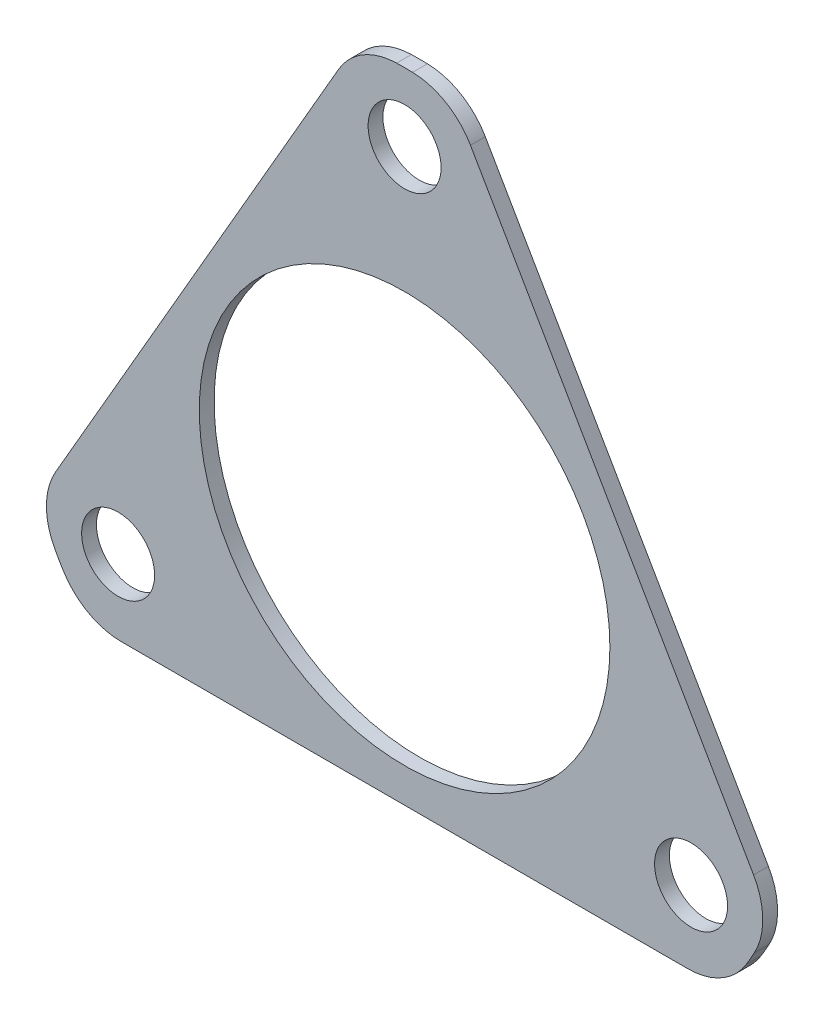
SolidWorks part; units mm, degrees
ref_plane "Спереди" through (0, 0, 0) normal (0, 0, 1) x (1, 0, 0)
ref_plane "Сверху" through (0, 0, 0) normal (0, 1, 0) x (1, 0, 0)
ref_plane "Справа" through (0, 0, 0) normal (1, 0, 0) x (0, 0, -1)
sketch "Sketch1" plane through (0, 0, 0) normal (0, 0, 1) x (1, 0, 0)
  line L0 (3.9, 6.755) -> (7.8, 0) construction
  line L2 (5.85, 10.1325) -> (11.7, 0) construction
  line L4 (7.8, 13.51) -> (15.6, 0) construction
  circle A61 centre (0, 0) radius 20
  circle A131 centre (0, 0) radius 1.25
  circle A484 centre (3.9, 0) radius 1.25
  circle A485 centre (7.8, 0) radius 1.25
  circle A486 centre (11.7, 0) radius 1.25
  circle A487 centre (15.6, 0) radius 1.25
  circle A488 centre (1.95, -3.3775) radius 1.25
  circle A489 centre (3.9, -6.755) radius 1.25
  circle A490 centre (5.85, -10.1325) radius 1.25
  circle A491 centre (7.8, -13.51) radius 1.25
  circle A492 centre (-1.95, -3.3775) radius 1.25
  circle A493 centre (-3.9, -6.755) radius 1.25
  circle A494 centre (-5.85, -10.1325) radius 1.25
  circle A495 centre (-7.8, -13.51) radius 1.25
  circle A496 centre (-3.9, 0) radius 1.25
  circle A497 centre (-7.8, 0) radius 1.25
  circle A498 centre (-11.7, 0) radius 1.25
  circle A499 centre (-15.6, 0) radius 1.25
  circle A500 centre (-1.95, 3.3775) radius 1.25
  circle A501 centre (-3.9, 6.755) radius 1.25
  circle A502 centre (-5.85, 10.1325) radius 1.25
  circle A503 centre (-7.8, 13.51) radius 1.25
  circle A504 centre (1.95, 3.3775) radius 1.25
  circle A505 centre (3.9, 6.755) radius 1.25
  circle A506 centre (5.85, 10.1325) radius 1.25
  circle A507 centre (7.8, 13.51) radius 1.25
  circle A508 centre (5.85, 3.3775) radius 1.25
  circle A509 centre (7.8, 6.755) radius 1.25
  circle A510 centre (9.75, 3.3775) radius 1.25
  circle A511 centre (11.7, 6.755) radius 1.25
  circle A512 centre (9.7491, 10.1341) radius 1.25
  circle A513 centre (13.6509, 3.3759) radius 1.25
  circle A514 centre (5.85, -3.3791) radius 1.25
  circle A515 centre (9.75, -3.3791) radius 1.25
  circle A516 centre (7.8, -6.7566) radius 1.25
  circle A517 centre (11.7, -6.7566) radius 1.25
  circle A518 centre (9.7491, -10.1356) radius 1.25
  circle A519 centre (13.6509, -3.3775) radius 1.25
  circle A520 centre (-0.0013, -6.7573) radius 1.25
  circle A521 centre (1.9487, -10.1348) radius 1.25
  circle A522 centre (-1.9513, -10.1348) radius 1.25
  circle A523 centre (-0.0013, -13.5123) radius 1.25
  circle A524 centre (-3.9032, -13.5123) radius 1.25
  circle A525 centre (3.9005, -13.5123) radius 1.25
  circle A526 centre (-5.8527, -3.3791) radius 1.25
  circle A527 centre (-7.8027, -6.7566) radius 1.25
  circle A528 centre (-9.7527, -3.3791) radius 1.25
  circle A529 centre (-11.7027, -6.7566) radius 1.25
  circle A530 centre (-13.6536, -3.3775) radius 1.25
  circle A531 centre (-9.7518, -10.1356) radius 1.25
  circle A532 centre (-5.8527, 3.3775) radius 1.25
  circle A533 centre (-9.7527, 3.3775) radius 1.25
  circle A534 centre (-7.8027, 6.755) radius 1.25
  circle A535 centre (-11.7027, 6.755) radius 1.25
  circle A536 centre (-9.7518, 10.1341) radius 1.25
  circle A537 centre (-13.6536, 3.3759) radius 1.25
  circle A538 centre (-0.0014, 6.7558) radius 1.25
  circle A539 centre (-1.9514, 10.1333) radius 1.25
  circle A540 centre (1.9486, 10.1333) radius 1.25
  circle A541 centre (-0.0014, 13.5108) radius 1.25
  circle A542 centre (3.9005, 13.5108) radius 1.25
  circle A543 centre (-3.9032, 13.5108) radius 1.25
  circle A544 centre (13.65, -1.1258) radius 2.2517 construction
  circle A545 centre (11.7009, -4.5044) radius 2.2522 construction
  circle A546 centre (9.75, -7.8834) radius 2.2522 construction
  circle A547 centre (7.7987, -11.2591) radius 2.2509 construction
  circle A548 centre (13.65, -1.1258) radius 0.65
  circle A549 centre (11.7009, -4.5044) radius 0.65
  circle A550 centre (9.75, -7.8834) radius 0.65
  circle A551 centre (7.7987, -11.2591) radius 0.65
  circle A552 centre (9.75, -1.1258) radius 0.65
  circle A553 centre (7.8009, -4.5044) radius 0.65
  circle A554 centre (5.85, -7.8834) radius 0.65
  circle A555 centre (3.8987, -11.2591) radius 0.65
  circle A556 centre (5.85, -1.1258) radius 0.65
  circle A557 centre (3.9009, -4.5044) radius 0.65
  circle A558 centre (1.95, -7.8834) radius 0.65
  circle A559 centre (-0.0013, -11.2591) radius 0.65
  circle A560 centre (1.95, -1.1258) radius 0.65
  circle A561 centre (0.0009, -4.5044) radius 0.65
  circle A562 centre (-1.95, -7.8834) radius 0.65
  circle A563 centre (-3.9013, -11.2591) radius 0.65
  circle A564 centre (-1.95, -1.1258) radius 0.65
  circle A565 centre (-3.8991, -4.5044) radius 0.65
  circle A566 centre (-5.85, -7.8834) radius 0.65
  circle A567 centre (-7.8013, -11.2591) radius 0.65
  circle A568 centre (-5.85, -1.1258) radius 0.65
  circle A569 centre (-7.7991, -4.5044) radius 0.65
  circle A570 centre (-9.75, -7.8834) radius 0.65
  circle A572 centre (-9.75, -1.1258) radius 0.65
  circle A573 centre (-11.6991, -4.5044) radius 0.65
  circle A576 centre (-13.65, -1.1258) radius 0.65
  circle A587 centre (0, 2.2517) radius 2.2517 construction
  circle A588 centre (0, 2.2517) radius 0.65
  circle A589 centre (3.9, 2.2517) radius 0.65
  circle A590 centre (7.8, 2.2517) radius 0.65
  circle A591 centre (11.7, 2.2517) radius 0.65
  circle A592 centre (15.6, 2.2517) radius 0.65
  circle A593 centre (1.9491, 5.6297) radius 2.2522 construction
  circle A594 centre (1.9491, 5.6297) radius 0.65
  circle A595 centre (5.8491, 5.6297) radius 0.65
  circle A596 centre (9.7491, 5.6297) radius 0.65
  circle A597 centre (13.6491, 5.6297) radius 0.65
  circle A598 centre (3.8991, 9.0072) radius 2.2522 construction
  circle A599 centre (3.8991, 9.0072) radius 0.65
  circle A600 centre (7.7991, 9.0072) radius 0.65
  circle A601 centre (11.6991, 9.0072) radius 0.65
  circle A602 centre (5.85, 12.3842) radius 2.2517 construction
  circle A603 centre (5.85, 12.3842) radius 0.65
  circle A604 centre (9.75, 12.3842) radius 0.65
  circle A605 centre (5.85, -14.6358) radius 0.65
  circle A606 centre (1.9509, -14.6353) radius 0.65
  circle A607 centre (-1.9491, -14.6353) radius 0.65
  circle A608 centre (-5.85, -14.6358) radius 0.65
  circle A609 centre (-15.6, 2.2517) radius 0.65
  circle A610 centre (-13.65, 5.6281) radius 0.65
  circle A611 centre (-11.7, 9.0056) radius 0.65
  circle A612 centre (-9.75, 12.3842) radius 0.65
  circle A613 centre (-5.85, 12.3842) radius 0.65
  circle A614 centre (-1.95, 12.3842) radius 0.65
  circle A615 centre (1.95, 12.3842) radius 0.65
  circle A616 centre (-7.8, 9.0056) radius 0.65
  circle A617 centre (-9.75, 5.6281) radius 0.65
  circle A618 centre (-11.7, 2.2517) radius 0.65
  circle A619 centre (-3.9, 9.0056) radius 0.65
  circle A620 centre (-5.85, 5.6281) radius 0.65
  circle A621 centre (-7.8, 2.2517) radius 0.65
  circle A622 centre (0, 9.0056) radius 0.65
  circle A623 centre (-1.95, 5.6281) radius 0.65
  circle A624 centre (-3.9, 2.2517) radius 0.65
  circle A625 centre (-15.5991, -4.5044) radius 0.65
  circle A626 centre (-13.65, -7.8834) radius 0.65
  circle A627 centre (-17.55, -7.8834) radius 0.65
  circle A628 centre (-19.5013, -11.2591) radius 0.65
  circle A629 centre (-15.6013, -11.2591) radius 0.65
  circle A630 centre (-11.7013, -11.2591) radius 0.65
  point P51 (0, 0)
  point P125 (-0.0013, -0.0008)
  point P231 (0, 0)
  dimension "D1" = 5
  dimension "D3" = 6
  dimension "D5" = 8
  dimension "D7" = 4
  dimension "D11" = 4
  dimension "D2" = 6
  dimension "D6" = 5
  dimension "D8" = 3
  dimension "D9" = 2
  dimension "D4" = 1.3
  dimension "D10" = 3
ref_plane "Plane1" through (0, 0, 10) normal (0, 0, 1) x (1, 0, 0)
sketch "Sketch2" plane through (0, 0, 10) normal (0, 0, 1) x (1, 0, 0)
  line L0 (0, 0.2409) -> (0, 17)
  line L62 (0.1416, 0.1949) -> (9.9923, 13.7533)
  line L71 (0.2291, 0.0744) -> (16.168, 5.2533)
  line L92 (0.2291, -0.0744) -> (16.168, -5.2533)
  line L101 (0.1416, -0.1949) -> (9.9923, -13.7533)
  line L110 (0, -0.2409) -> (0, -17)
  line L119 (-0.1416, -0.1949) -> (-9.9923, -13.7533)
  line L124 (-0.2291, -0.0744) -> (-16.168, -5.2533)
  line L133 (-0.2291, 0.0744) -> (-16.168, 5.2533)
  line L142 (-0.1416, 0.1949) -> (-9.9923, 13.7533)
  line L183 (0.5, -0.2001) -> (0.5, 16.4924)
  line L185 (9.4541, 13.5229) -> (0.0202, 0.5382)
  line L186 (15.7825, -4.8126) -> (0.5181, 0.1471)
  line L187 (-0.0358, -0.5374) -> (15.8397, 4.6209)
  line L188 (0.3, -16.4973) -> (0.3, -0.4473)
  line L189 (-0.5221, -0.132) -> (9.2895, -13.6365)
  line L190 (-15.5971, -5.3833) -> (-0.3327, -0.4235)
  line L191 (-0.2869, 0.4558) -> (-10.0985, -13.0488)
  line L192 (-9.9396, 13.1702) -> (-0.5056, 0.1855)
  line L193 (0.3448, 0.4137) -> (-15.5307, 5.572)
  circle A52 centre (0, 0) radius 17
  circle A53 centre (0, 0) radius 18
  circle A199 centre (0, 0) radius 0.2409
  circle A246 centre (0, 0) radius 0.5386
  circle A247 centre (0, 0) radius 16.5
  point P39 (0, 0)
  point P80 (0, 0)
  point P108 (0, 0)
  dimension "D1" = 10
  dimension "D4" = 5
  dimension "D2" = 0.5
  dimension "D5" = 1
  dimension "D6" = 36
  dimension "D7" = 0.5
  dimension "D3" = 0.3
extrude "Boss-Extrude1" add sketch "Sketch2" against normal blind 1.3 contours A53 A52 | L187 A247 L71 A199 | L62 A247 L185 A199 | L183 A247 L0 A199 | L142 A247 L192 A199 | L193 A247 L133 A199 | L124 A247 L190 A199 | L191 A247 L119 A199 | L110 A247 L188 A199 | L189 A247 L101 A199 | L92 A247 L186 A199 | A247 L62 A52 L0 | A247 L142 A52 L133 | A247 L124 A52 L119 | A247 L110 A52 L101 | A247 L92 A52 L71 | A246 L62 L183 L185 L0 | A246 L92 L187 L186 L71 | A246 L110 L189 L188 L101 | A246 L124 L191 L190 L119 | A246 L142 L193 L192 L133
sketch "Sketch11" plane through (0, 0, 8.7) normal (0, 0, -1) x (-1, 0, 0)
  line L0 (0, 0.5386) -> (0, 18)
  line L1 (0.3166, 0.4357) -> (10.702, 14.4729)
  line L2 (0.5122, -0.1664) -> (17.0717, -5.7059)
  line L3 (0.5122, 0.1664) -> (17.119, 5.5623)
  line L4 (0, -0.5386) -> (-0.1512, -17.9994)
  line L5 (0.3166, -0.4357) -> (10.5801, -14.5623)
  line L6 (-0.5122, -0.1664) -> (-17.1651, -5.4184)
  line L7 (-0.3166, -0.4357) -> (-10.5801, -14.5623)
  line L8 (-0.3166, 0.4357) -> (-10.4575, 14.6506)
  line L9 (-0.5122, 0.1664) -> (-17.119, 5.5623)
  circle A0 centre (0, 0) radius 0.5386
  arc A1 (0, 0.5386) -> (-0.3166, 0.4357) centre (0, 0) ccw construction
  arc A2 (-0.5122, 0.1664) -> (-0.5122, -0.1664) centre (0, 0) ccw construction
  circle A5 centre (0, 0) radius 18 construction
  arc A6 (0, 18) -> (10.702, 14.4729) centre (0, 0) cw
  arc A8 (17.119, 5.5623) -> (17.0717, -5.7059) centre (0, 0) cw
  arc A10 (10.5801, -14.5623) -> (-0.1512, -17.9994) centre (0, 0) cw
  arc A12 (-10.5801, -14.5623) -> (-17.1651, -5.4184) centre (0, 0) cw
  arc A14 (-17.119, 5.5623) -> (-10.4575, 14.6506) centre (0, 0) cw
  point P63 (0, 0)
  dimension "D1" = 5
extrude "Boss-Extrude7" add sketch "Sketch11" against normal blind 1.3
sketch "Sketch13" plane through (0, 0, 8.7) normal (0, 0, -1) x (-1, 0, 0)
  circle A0 centre (0, 0) radius 3.3
extrude "Boss-Extrude8" [suppressed] add sketch "Sketch13" against normal blind 3
sketch "Sketch14" plane through (0, 0, 10) normal (0, 0, 1) x (1, 0, 0)
  circle A0 centre (0, 0) radius 17
  circle A1 centre (0, 0) radius 17 construction
sketch "Sketch9" plane through (0, 0, 10) normal (0, 0, 1) x (1, 0, 0)
  circle A0 centre (0, 0) radius 3.0981
sketch "Sketch16" plane through (0, 0, 10) normal (0, 0, 1) x (1, 0, 0)
  circle A0 centre (0, 0) radius 3.3
sketch "Sketch17" plane through (0, 0, 8.7) normal (0, 0, -1) x (-1, 0, 0)
  circle A0 centre (0, 0) radius 0.7
extrude "Boss-Extrude9" add sketch "Sketch17" against normal up to surface (1.3 mm away) up to face at (3.3661, -10.6845, 10)
extrude "Boss-Extrude5" [suppressed] add sketch "Sketch9" against normal up to surface (10 mm away)
sketch "Sketch3" plane through (0, 0, 8.7) normal (0, 0, -1) x (-1, 0, 0)
  circle A0 centre (0, 0) radius 17.6
  circle A1 centre (0, 0) radius 35
  circle M33 centre (0, 0) radius 18
extrude "Boss-Extrude2" add sketch "Sketch3" against normal blind 1.3 contours A1 M33
sketch "Sketch4" plane through (0, 0, 8.7) normal (0, 0, -1) x (-1, 0, 0)
  circle A0 centre (0, 0) radius 29 construction
  circle A1 centre (0, 29) radius 3.2
  circle A2 centre (25.1147, -14.5) radius 3.2
  circle A3 centre (-25.1147, -14.5) radius 3.2
  point P11 (0, 0)
  dimension "D1" = 3
sketch "Sketch6" plane through (0, 0, 10) normal (0, 0, -1) x (-1, 0, 0)
  circle A0 centre (0, 30) radius 5
  circle A2 centre (25.9808, -15) radius 5
  circle A3 centre (-25.9808, -15) radius 5
  point P10 (0, 0)
  dimension "D1" = 3
extrude "Boss-Extrude4" add sketch "Sketch6" along normal blind 1
sketch "Sketch7" plane through (0, 0, 8.7) normal (0, 0, -1) x (-1, 0, 0)
  line L1 (0, 42) -> (-36.3731, -21)
  line L2 (-36.3731, -21) -> (36.3731, -21)
  line L3 (36.3731, -21) -> (0, 42)
  circle A2 centre (0, 0) radius 21 construction
  circle A3 centre (0, 0) radius 59.1314
extrude "Cut-Extrude1" cut sketch "Sketch7" against normal blind 10
fillet "Fillet1" radius 6 6 edges at (-32.1865, -13.7487, 9.35) (-4.1865, 34.7487, 9.35) (28, -21, 9.35) (-28, -21, 9.35) (4.1865, 34.7487, 9.35) (32.1865, -13.7487, 9.35)
extrude "Cut-Extrude2" cut sketch "Sketch4" against normal blind 10
sketch "Sketch18" plane through (0, 0, 10) normal (0, 0, 1) x (1, 0, 0)
  circle A0 centre (0, 0) radius 18
extrude "Cut-Extrude3" cut sketch "Sketch18" against normal blind 10
